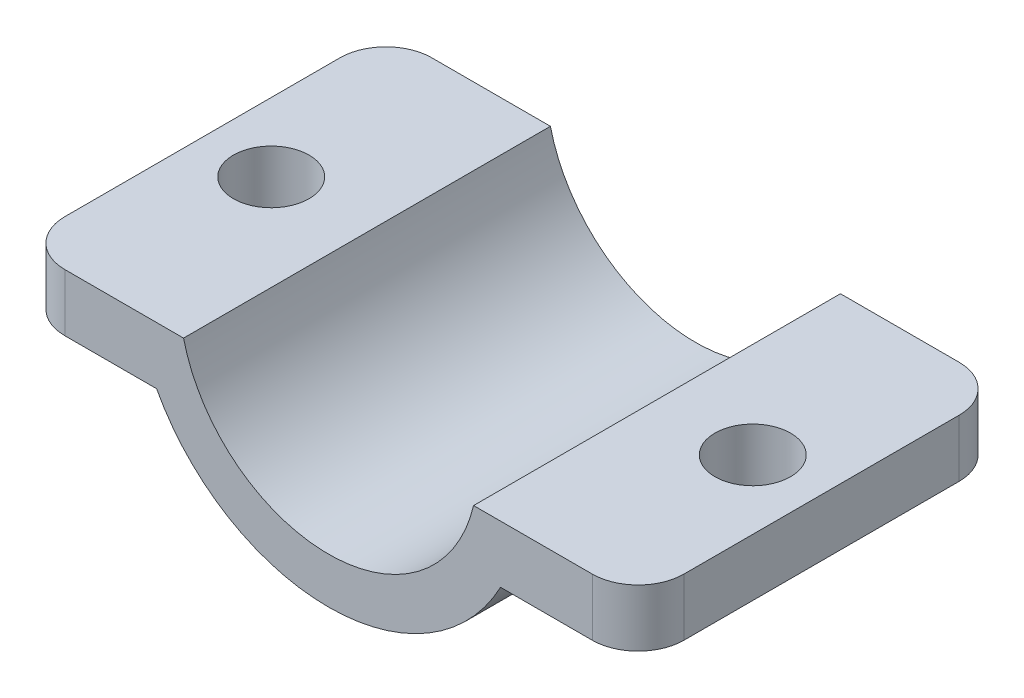
SolidWorks part; units mm, degrees
material "打印件"
ref_plane "前视基准面" through (0, 0, 0) normal (0, 0, 1) x (1, 0, 0)
ref_plane "上视基准面" through (0, 0, 0) normal (0, 1, 0) x (1, 0, 0)
ref_plane "右视基准面" through (0, 0, 0) normal (1, 0, 0) x (0, 0, -1)
sketch "草图1" plane through (0, 0, 0) normal (0, 0, 1) x (1, 0, 0)
  line L0 (-6.3246, -1.5) -> (-13.5, -1.5)
  line L1 (-13.5, -1.5) -> (-13.5, -4)
  line L2 (-13.5, -4) -> (-7.5, -4)
  line L3 (6.3246, -1.5) -> (13.5, -1.5)
  line L4 (13.5, -1.5) -> (13.5, -4)
  line L5 (13.5, -4) -> (7.5, -4)
  arc A0 (-6.3246, -1.5) -> (6.3246, -1.5) centre (0, 0) ccw
  arc A1 (-7.5, -4) -> (7.5, -4) centre (0, 0) ccw
  dimension "D1" = 6.5
  dimension "D2" = 8.5
  dimension "D3" = 2.5
  dimension "D4" = 6
  dimension "D5" = 1.5
extrude "凸台-拉伸1" add sketch "草图1" along normal blind 16
sketch "草图2" plane through (0, -4, 0) normal (0, -1, 0) x (1, 0, 0)
  line L0 (-10.5, 16) -> (-10.5, 0) construction
  line L1 (-13.5, 16) -> (-7.5, 16) construction
  line L2 (-13.5, 0) -> (-7.5, 0) construction
  line L3 (10.5, 16) -> (10.5, 0) construction
  line L4 (7.5, 16) -> (13.5, 16) construction
  line L5 (7.5, 0) -> (13.5, 0) construction
  circle A0 centre (-10.5, 8) radius 1.65
  circle A1 centre (10.5, 8) radius 1.65
  dimension "D1" = 3.3
extrude "切除-拉伸1" cut sketch "草图2" against normal through all
fillet "圆角1" radius 2 4 edges at (13.5, -2.75, 16) (-13.5, -2.75, 16) (13.5, -2.75, 0) (-13.5, -2.75, 0)
